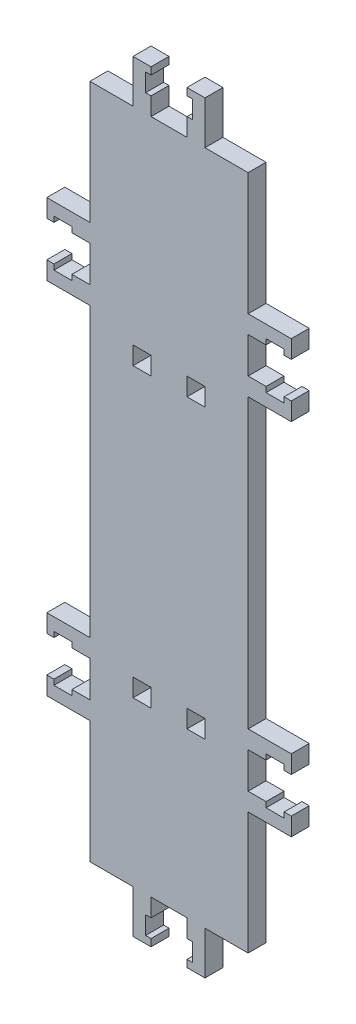
SolidWorks part; units mm, degrees
ref_plane "Plan de face" through (0, 0, 0) normal (0, 0, 1) x (1, 0, 0)
ref_plane "Plan de dessus" through (0, 0, 0) normal (0, 1, 0) x (1, 0, 0)
ref_plane "Plan de droite" through (0, 0, 0) normal (1, 0, 0) x (0, 0, -1)
sketch "Esquisse1" plane through (0, 0, 0) normal (0, 0, 1) x (1, 0, 0)
  line L0 (0, 0) -> (0, 94) construction
  line L1 (-24.1872, 94) -> (25.2472, 94) construction
  line L2 (-10, 188) -> (-22, 188)
  line L3 (-22, 188) -> (-22, 0) construction
  line L4 (-22, 0) -> (-10, 0)
  line L5 (10, 0) -> (22, 0)
  line L6 (-22, 0) -> (-22, 34)
  line L7 (22, 0) -> (22, 188) construction
  line L8 (-22, 54) -> (-22, 134)
  line L9 (22, 188) -> (10, 188)
  line L10 (22, 0) -> (22, 34)
  line L11 (-22, 154) -> (-22, 188)
  line L12 (22, 54) -> (22, 134)
  line L13 (22, 154) -> (22, 188)
  point P13 (12.5549, 127.7564)
  point P15 (5, 44.7398)
  line B0 (0, 188) -> (0, 176.135) construction
  line B1 (0, 188) -> (-5, 188)
  line B2 (-5, 193) -> (-10, 193) construction
  line B3 (-10, 193) -> (-10, 188)
  line B4 (-5, 193) -> (-5, 188)
  line B5 (0, 188) -> (5, 188)
  line B6 (5, 188) -> (5, 193)
  line B7 (5, 193) -> (10, 193) construction
  line B8 (10, 193) -> (10, 188)
  line B9 (-10, 193) -> (-10, 200)
  line B10 (-10, 200) -> (-5, 200)
  line B11 (-5, 200) -> (-5, 198)
  line B12 (-5, 198) -> (-6.5, 198)
  line B13 (-6.5, 198) -> (-6.5, 193)
  line B14 (-6.5, 193) -> (-5, 193)
  line B15 (5, 198) -> (6.5, 198)
  line B16 (10, 200) -> (5, 200)
  line B17 (5, 200) -> (5, 198)
  line B18 (6.5, 198) -> (6.5, 193)
  line B19 (10, 193) -> (10, 200)
  line B20 (10, 193) -> (10, 188)
  line B21 (5, 193) -> (6.5, 193)
  line B22 (0, 0) -> (0, 11.865) construction
  line B23 (0, 0) -> (-5, 0)
  line B24 (-5, -5) -> (-10, -5) construction
  line B25 (-10, -5) -> (-10, 0)
  line B26 (-5, -5) -> (-5, 0)
  line B27 (0, 0) -> (5, 0)
  line B28 (5, 0) -> (5, -5)
  line B29 (5, -5) -> (10, -5) construction
  line B30 (10, -5) -> (10, 0)
  line B31 (-10, -5) -> (-10, -12)
  line B32 (-10, -12) -> (-5, -12)
  line B33 (-5, -12) -> (-5, -10)
  line B34 (-5, -10) -> (-6.5, -10)
  line B35 (-6.5, -10) -> (-6.5, -5)
  line B36 (-6.5, -5) -> (-5, -5)
  line B37 (5, -10) -> (6.5, -10)
  line B38 (10, -12) -> (5, -12)
  line B39 (5, -12) -> (5, -10)
  line B40 (6.5, -10) -> (6.5, -5)
  line B41 (10, -5) -> (10, -12)
  line B42 (10, -5) -> (10, 0)
  line B43 (5, -5) -> (6.5, -5)
  line B44 (-22, 144) -> (-10.135, 144) construction
  line B45 (-22, 144) -> (-22, 139)
  line B46 (-27, 139) -> (-27, 134) construction
  line B47 (-27, 134) -> (-22, 134)
  line B48 (-27, 139) -> (-22, 139)
  line B49 (-22, 144) -> (-22, 149)
  line B50 (-22, 149) -> (-27, 149)
  line B51 (-27, 149) -> (-27, 154) construction
  line B52 (-27, 154) -> (-22, 154)
  line B53 (-27, 134) -> (-34, 134)
  line B54 (-34, 134) -> (-34, 139)
  line B55 (-34, 139) -> (-32, 139)
  line B56 (-32, 139) -> (-32, 137.5)
  line B57 (-32, 137.5) -> (-27, 137.5)
  line B58 (-27, 137.5) -> (-27, 139)
  line B59 (-32, 149) -> (-32, 150.5)
  line B60 (-34, 154) -> (-34, 149)
  line B61 (-34, 149) -> (-32, 149)
  line B62 (-32, 150.5) -> (-27, 150.5)
  line B63 (-27, 154) -> (-34, 154)
  line B64 (-27, 154) -> (-22, 154)
  line B65 (-27, 149) -> (-27, 150.5)
  line B66 (-22, 44) -> (-10.135, 44) construction
  line B67 (-22, 44) -> (-22, 49)
  line B68 (-27, 49) -> (-27, 54) construction
  line B69 (-27, 54) -> (-22, 54)
  line B70 (-27, 49) -> (-22, 49)
  line B71 (-22, 44) -> (-22, 39)
  line B72 (-22, 39) -> (-27, 39)
  line B73 (-27, 39) -> (-27, 34) construction
  line B74 (-27, 34) -> (-22, 34)
  line B75 (-27, 54) -> (-34, 54)
  line B76 (-34, 54) -> (-34, 49)
  line B77 (-34, 49) -> (-32, 49)
  line B78 (-32, 49) -> (-32, 50.5)
  line B79 (-32, 50.5) -> (-27, 50.5)
  line B80 (-27, 50.5) -> (-27, 49)
  line B81 (-32, 39) -> (-32, 37.5)
  line B82 (-34, 34) -> (-34, 39)
  line B83 (-34, 39) -> (-32, 39)
  line B84 (-32, 37.5) -> (-27, 37.5)
  line B85 (-27, 34) -> (-34, 34)
  line B86 (-27, 34) -> (-22, 34)
  line B87 (-27, 39) -> (-27, 37.5)
  line B88 (22, 44) -> (10.135, 44) construction
  line B89 (22, 44) -> (22, 49)
  line B90 (27, 49) -> (27, 54) construction
  line B91 (27, 54) -> (22, 54)
  line B92 (27, 49) -> (22, 49)
  line B93 (22, 44) -> (22, 39)
  line B94 (22, 39) -> (27, 39)
  line B95 (27, 39) -> (27, 34) construction
  line B96 (27, 34) -> (22, 34)
  line B97 (27, 54) -> (34, 54)
  line B98 (34, 54) -> (34, 49)
  line B99 (34, 49) -> (32, 49)
  line B100 (32, 49) -> (32, 50.5)
  line B101 (32, 50.5) -> (27, 50.5)
  line B102 (27, 50.5) -> (27, 49)
  line B103 (32, 39) -> (32, 37.5)
  line B104 (34, 34) -> (34, 39)
  line B105 (34, 39) -> (32, 39)
  line B106 (32, 37.5) -> (27, 37.5)
  line B107 (27, 34) -> (34, 34)
  line B108 (27, 34) -> (22, 34)
  line B109 (27, 39) -> (27, 37.5)
  line B110 (22, 144) -> (10.135, 144) construction
  line B111 (22, 144) -> (22, 139)
  line B112 (27, 139) -> (27, 134) construction
  line B113 (27, 134) -> (22, 134)
  line B114 (27, 139) -> (22, 139)
  line B115 (22, 144) -> (22, 149)
  line B116 (22, 149) -> (27, 149)
  line B117 (27, 149) -> (27, 154) construction
  line B118 (27, 154) -> (22, 154)
  line B119 (27, 134) -> (34, 134)
  line B120 (34, 134) -> (34, 139)
  line B121 (34, 139) -> (32, 139)
  line B122 (32, 139) -> (32, 137.5)
  line B123 (32, 137.5) -> (27, 137.5)
  line B124 (27, 137.5) -> (27, 139)
  line B125 (32, 149) -> (32, 150.5)
  line B126 (34, 154) -> (34, 149)
  line B127 (34, 149) -> (32, 149)
  line B128 (32, 150.5) -> (27, 150.5)
  line B129 (27, 154) -> (34, 154)
  line B130 (27, 154) -> (22, 154)
  line B131 (27, 149) -> (27, 150.5)
  line B132 (5, 128) -> (-5, 128) construction
  line B133 (5, 130.5) -> (10, 130.5)
  line B134 (5, 130.5) -> (5, 125.5)
  line B135 (5, 125.5) -> (10, 125.5)
  line B136 (10, 130.5) -> (10, 125.5)
  line B137 (-5, 130.5) -> (-10, 130.5)
  line B138 (-5, 130.5) -> (-5, 125.5)
  line B139 (-5, 125.5) -> (-10, 125.5)
  line B140 (-10, 130.5) -> (-10, 125.5)
  line B141 (0, 128) -> (0, 134.9724) construction
  circle B142 centre (0, 128) radius 2 construction
  line B143 (5, 48) -> (-5, 48) construction
  line B144 (5, 50.5) -> (10, 50.5)
  line B145 (5, 50.5) -> (5, 45.5)
  line B146 (5, 45.5) -> (10, 45.5)
  line B147 (10, 50.5) -> (10, 45.5)
  line B148 (-5, 50.5) -> (-10, 50.5)
  line B149 (-5, 50.5) -> (-5, 45.5)
  line B150 (-5, 45.5) -> (-10, 45.5)
  line B151 (-10, 50.5) -> (-10, 45.5)
  line B152 (0, 48) -> (0, 54.9724) construction
  circle B153 centre (0, 48) radius 2 construction
  dimension "D3" = 80
  dimension "D2" = 57.5
  dimension "D1" = 22
  dimension "D4" = 188
  dimension "D7" = 50
sketch_block_instance "Insert plots ep 5mm avec ergots-8"
sketch_block "Insert plots ep 5mm avec ergots" parameters "D1"=10, "D2"=5, "D3"=5, "D4"=5, "D5"=2, "D6"=1.5, "D7"=2, "D8"=2, "D9"=2.0716, "D10"=2
sketch_block_instance "Insert plots ep 5mm avec ergots-9"
sketch_block_instance "Insert plots ep 5mm avec ergots-11"
sketch_block_instance "Insert plots ep 5mm avec ergots-12"
sketch_block_instance "Insert plots ep 5mm avec ergots-15"
sketch_block_instance "Insert plots ep 5mm avec ergots-16"
sketch_block_instance "Trou M4 plots 5mm-11"
sketch_block "Trou M4 plots 5mm" parameters "D2"=4, "D5"=4, "D1"=5, "D3"=5, "D4"=10
sketch_block_instance "Trou M4 plots 5mm-12"
extrude "Boss.-Extru.1" add sketch "Esquisse1" along normal blind 5
